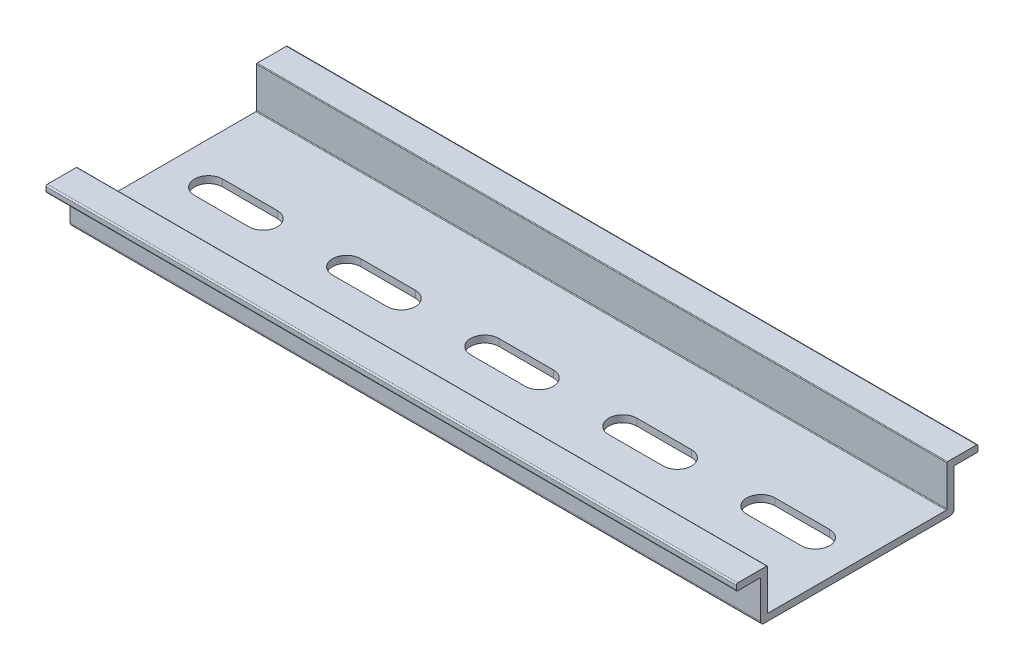
SolidWorks part; units mm, degrees
material "5052-H32"
ref_plane "Front Plane" through (0, 0, 0) normal (0, 0, 1) x (1, 0, 0)
ref_plane "Top Plane" through (0, 0, 0) normal (0, 1, 0) x (1, 0, 0)
ref_plane "Right Plane" through (0, 0, 0) normal (1, 0, 0) x (0, 0, -1)
sketch "HalfProfileS" plane through (0, 0, 0) normal (1, 0, 0) x (0, 0, -1)
  line L0 (-13.5, 0) -> (0, 0)
  line L6 (-14, 0.5) -> (-14, 5.9)
  line L8 (-14.1, 6) -> (-17.3, 6)
  line L9 (-17.5, 6.2) -> (-17.5, 6.8)
  line L10 (-17.3, 7) -> (-13.1, 7)
  line L11 (-13, 1.1) -> (-13, 6.9)
  line L12 (0, 0) -> (0, 1) construction
  line L13 (0, 1) -> (-12.9, 1)
  line L18 (-14, 3.2) -> (-13, 3.2) construction
  line L19 (-15.7, 6) -> (-15.7, 7) construction
  arc A0 (-13.1, 7) -> (-13, 6.9) centre (-13.1, 6.9) cw
  arc A2 (-17.5, 6.2) -> (-17.3, 6) centre (-17.3, 6.2) ccw
  arc A3 (-17.3, 7) -> (-17.5, 6.8) centre (-17.3, 6.8) ccw
  arc A17 (-14, 0.5) -> (-13.5, 0) centre (-13.5, 0.5) ccw
  arc A18 (-14.1, 6) -> (-14, 5.9) centre (-14.1, 5.9) cw
  arc A19 (-13, 1.1) -> (-12.9, 1) centre (-12.9, 1.1) ccw
  dimension "R3" = 0.2
  dimension "R1" = 0.1
  dimension "LowerBaseRadius" = 0.5
  dimension "R2" = 0.1
  dimension "R4" = 0.1
  dimension "ConstantWallThickness" = 1
  dimension "Height" = 7
  dimension "UpperFlatRibWidth" = 4.5
  dimension "DinRailGrippingWidth" = 35
sketch "ProfileS" plane through (0, 0, 0) normal (1, 0, 0) x (0, 0, -1)
  line L66 (-13.5, 0) -> (0, 0) construction
  line L72 (-14, 0.5) -> (-14, 5.9) construction
  line L73 (-14.1, 6) -> (-17.3, 6) construction
  line L74 (-17.5, 6.2) -> (-17.5, 6.8) construction
  line L75 (-17.3, 7) -> (-13.1, 7) construction
  line L76 (-13, 1.1) -> (-13, 6.9) construction
  line L77 (0, 1) -> (-12.9, 1) construction
  line L78 (-13.5, 0) -> (13.5, 0)
  line L79 (-14, 0.5) -> (-14, 5.9)
  line L80 (-14.1, 6) -> (-17.3, 6)
  line L81 (-17.5, 6.2) -> (-17.5, 6.8)
  line L82 (-17.3, 7) -> (-13.1, 7)
  line L83 (-13, 1.1) -> (-13, 6.9)
  line L84 (12.9, 1) -> (-12.9, 1)
  line L85 (0, 0) -> (0, 1) construction
  line L86 (13, 1.1) -> (13, 6.9)
  line L87 (17.3, 7) -> (13.1, 7)
  line L88 (17.5, 6.2) -> (17.5, 6.8)
  line L89 (14.1, 6) -> (17.3, 6)
  line L90 (14, 0.5) -> (14, 5.9)
  arc A66 (-14, 0.5) -> (-13.5, 0) centre (-13.5, 0.5) ccw construction
  arc A67 (-14, 5.9) -> (-14.1, 6) centre (-14.1, 5.9) ccw construction
  arc A68 (-17.5, 6.2) -> (-17.3, 6) centre (-17.3, 6.2) ccw construction
  arc A69 (-17.3, 7) -> (-17.5, 6.8) centre (-17.3, 6.8) ccw construction
  arc A70 (-13, 6.9) -> (-13.1, 7) centre (-13.1, 6.9) ccw construction
  arc A71 (-13, 1.1) -> (-12.9, 1) centre (-12.9, 1.1) ccw construction
  arc A72 (-14, 0.5) -> (-13.5, 0) centre (-13.5, 0.5) ccw
  arc A73 (-14, 5.9) -> (-14.1, 6) centre (-14.1, 5.9) ccw
  arc A74 (-17.5, 6.2) -> (-17.3, 6) centre (-17.3, 6.2) ccw
  arc A75 (-17.3, 7) -> (-17.5, 6.8) centre (-17.3, 6.8) ccw
  arc A76 (-13, 6.9) -> (-13.1, 7) centre (-13.1, 6.9) ccw
  arc A77 (-13, 1.1) -> (-12.9, 1) centre (-12.9, 1.1) ccw
  arc A78 (13, 1.1) -> (12.9, 1) centre (12.9, 1.1) cw
  arc A79 (13, 6.9) -> (13.1, 7) centre (13.1, 6.9) cw
  arc A80 (17.3, 7) -> (17.5, 6.8) centre (17.3, 6.8) cw
  arc A81 (17.5, 6.2) -> (17.3, 6) centre (17.3, 6.2) cw
  arc A82 (14, 5.9) -> (14.1, 6) centre (14.1, 5.9) cw
  arc A83 (14, 0.5) -> (13.5, 0) centre (13.5, 0.5) cw
extrude "Profile" add sketch "ProfileS" along normal mid plane 100
sketch "SlotS" plane through (0, 0, 0) normal (0, 1, 0) x (1, 0, 0)
  line L0 (-3.95, 0) -> (3.95, 0) construction
  line L1 (-3.95, 2.05) -> (3.95, 2.05)
  line L2 (-3.95, -2.05) -> (3.95, -2.05)
  line L3 (-3.95, 0) -> (-6, 0) construction
  line L4 (3.95, 0) -> (6, 0) construction
  arc A0 (-3.95, 2.05) -> (-3.95, -2.05) centre (-3.95, 0) ccw
  arc A1 (3.95, -2.05) -> (3.95, 2.05) centre (3.95, 0) ccw
  point P2 (0, 0)
  point P3 (0, 0)
  dimension "Width" = 4.1
  dimension "TotalLength" = 12
extrude "Slot" cut sketch "SlotS" along normal through all
pattern_linear "SlotLP" count 3 spacing 20 along (-1, 0, 0) of "Slot"
mirror "SlotHP" about plane through (0, 0, 0) normal (1, 0, 0) of "SlotLP"
